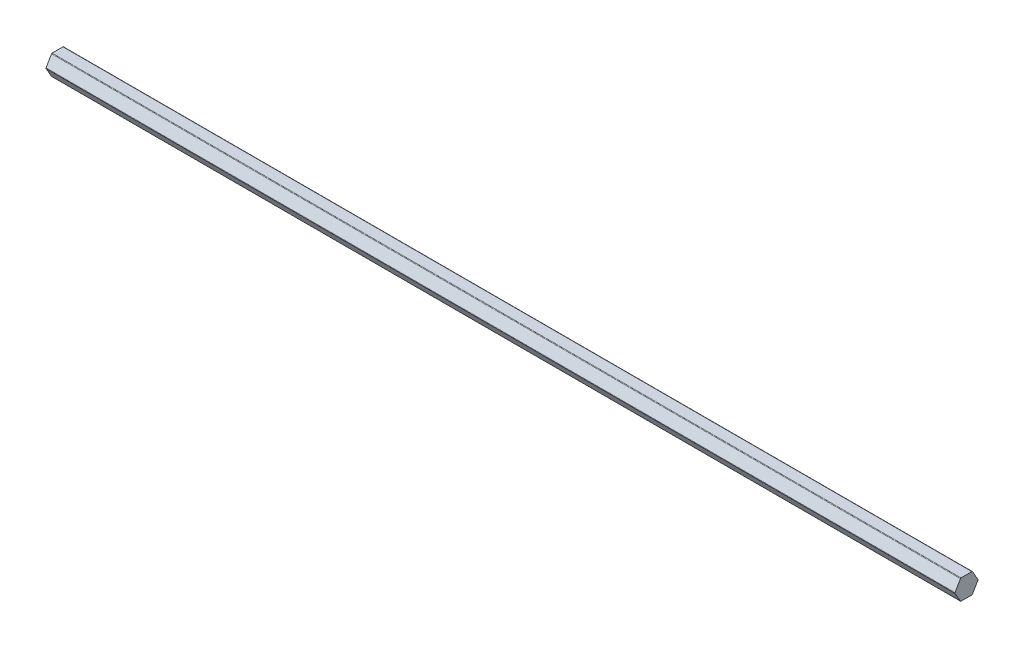
SolidWorks part; units mm, degrees
ref_plane "Front Plane" through (0, 0, 0) normal (0, 0, 1) x (1, 0, 0)
ref_plane "Top Plane" through (0, 0, 0) normal (0, 1, 0) x (1, 0, 0)
ref_plane "Right Plane" through (0, 0, 0) normal (1, 0, 0) x (0, 0, -1)
sketch "Sketch1" plane through (0, 0, 0) normal (1, 0, 0) x (0, 0, -1)
  line L1 (7.188, 0.25) -> (3.8105, 6.1)
  line L2 (3.3775, 6.35) -> (-3.3775, 6.35)
  line L3 (-3.8105, 6.1) -> (-7.188, 0.25)
  line L4 (-7.188, -0.25) -> (-3.8105, -6.1)
  line L5 (-3.3775, -6.35) -> (3.3775, -6.35)
  line L6 (3.8105, -6.1) -> (7.188, -0.25)
  circle A0 centre (0, 0) radius 6.35 construction
  arc A1 (-3.8105, -6.1) -> (-3.3775, -6.35) centre (-3.3775, -5.85) ccw
  arc A2 (3.3775, -6.35) -> (3.8105, -6.1) centre (3.3775, -5.85) ccw
  arc A3 (7.188, 0.25) -> (7.188, -0.25) centre (6.755, 0) cw
  arc A4 (3.8105, 6.1) -> (3.3775, 6.35) centre (3.3775, 5.85) ccw
  arc A5 (-7.188, 0.25) -> (-7.188, -0.25) centre (-6.755, 0) ccw
  arc A6 (-3.3775, 6.35) -> (-3.8105, 6.1) centre (-3.3775, 5.85) ccw
  point P1 (0, 0)
  point P16 (7.3323, 0)
  point P23 (-3.6662, 6.35)
  dimension "D2" = 0.5
  dimension "D1" = 12.7
extrude "Boss-Extrude1" add sketch "Sketch1" along normal mid plane 571.5
equation "\"SHAFT_LENGHT\"= 22.5in"
equation "\"D1@Boss-Extrude1\"=\"SHAFT_LENGHT\""
